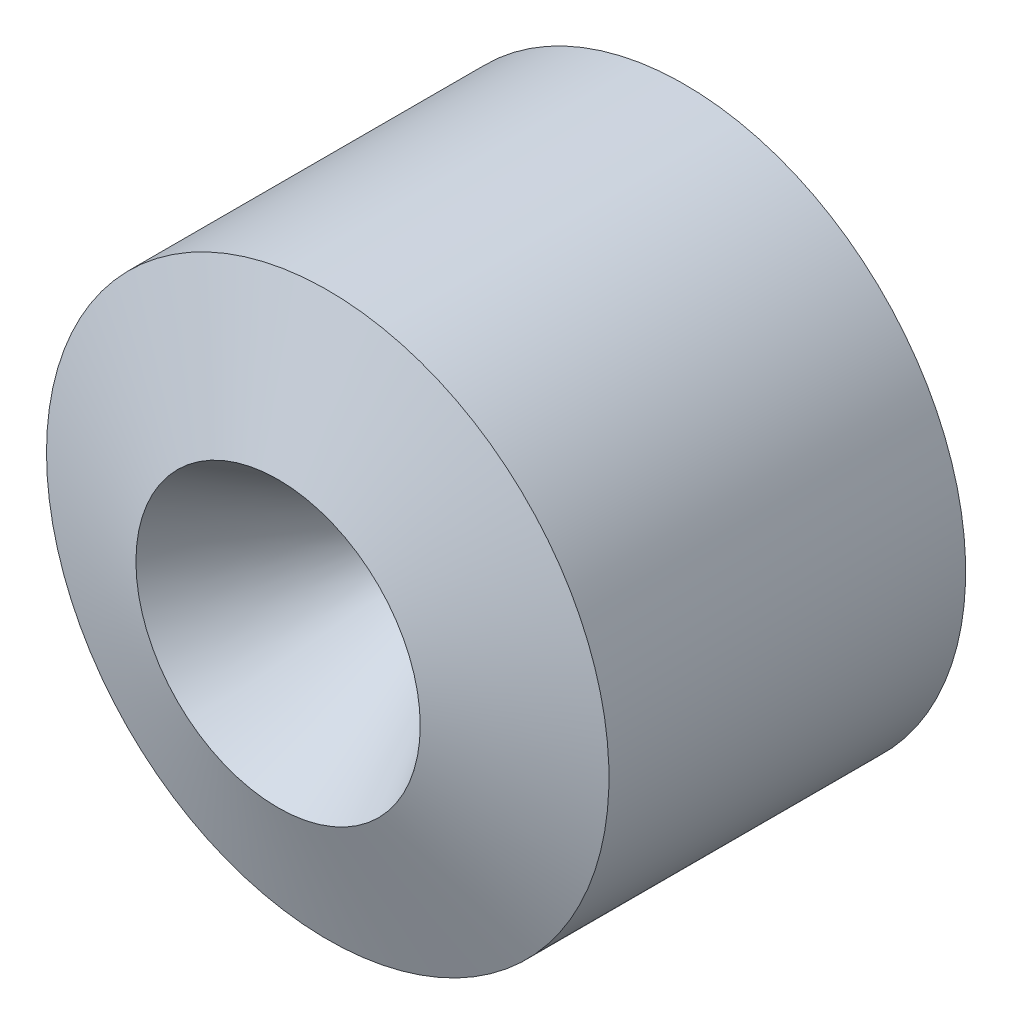
SolidWorks part; units mm, degrees
ref_plane "Front Plane" through (0, 0, 0) normal (0, 0, 1) x (1, 0, 0)
ref_plane "Top Plane" through (0, 0, 0) normal (0, 1, 0) x (1, 0, 0)
ref_plane "Right Plane" through (0, 0, 0) normal (1, 0, 0) x (0, 0, -1)
sketch "Sketch1" plane through (0, 0, 0) normal (1, 0, 0) x (0, 0, -1)
  line L0 (0, 0) -> (-13.9375, 8.4935)
  line L1 (-13.9375, 8.4935) -> (-10.9703, 16.8036)
  line L2 (-10.9703, 16.8036) -> (10.3414, 16.8036)
  line L3 (10.3414, 16.8036) -> (10.3414, 0)
  line L4 (10.3414, 0) -> (0, 0)
revolve "Revolve1" add sketch "Sketch1" angle 360 about L4
